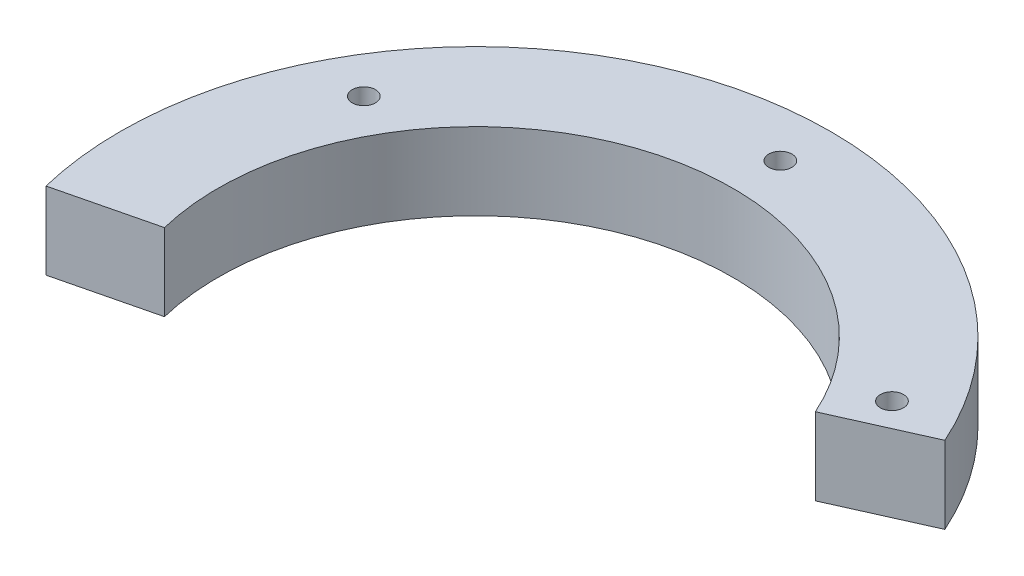
SolidWorks part; units mm, degrees
material "PLA"
ref_plane "Front Plane" through (0, 0, 0) normal (0, 0, 1) x (1, 0, 0)
ref_plane "Top Plane" through (0, 0, 0) normal (0, 1, 0) x (1, 0, 0)
ref_plane "Right Plane" through (0, 0, 0) normal (1, 0, 0) x (0, 0, -1)
sketch "Sketch1" plane through (0, 0, 0) normal (0, 1, 0) x (1, 0, 0)
  circle A0 centre (0, 0) radius 39.5 construction
  circle A1 centre (0, 39.5) radius 1.5
  circle A2 centre (34.208, 19.75) radius 1.5
  circle A3 centre (34.208, -19.75) radius 1.5
  circle A4 centre (0, -39.5) radius 1.5
  circle A5 centre (-34.208, -19.75) radius 1.5
  circle A6 centre (-34.208, 19.75) radius 1.5
  circle A7 centre (0, 0) radius 33.3375
  circle A8 centre (0, 0) radius 46.0375
  point P17 (0, 0)
  dimension "D1" = 79
  dimension "D2" = 3
  dimension "D4" = 66.675
  dimension "D5" = 92.075
  dimension "D3" = 6
extrude "Boss-Extrude1" add sketch "Sketch1" along normal blind 10
sketch "Sketch2" plane through (0, 10, 0) normal (0, 1, 0) x (1, 0, 0)
  line L0 (0, 0) -> (-44.7262, -10.9097)
  line L1 (0, 0) -> (42.0297, 18.787)
  circle A0 centre (0, 0) radius 46.0375 construction
  arc A1 (-44.7262, -10.9097) -> (42.0297, 18.787) centre (0, 0) ccw
extrude "Cut-Extrude1" cut sketch "Sketch2" against normal through all
